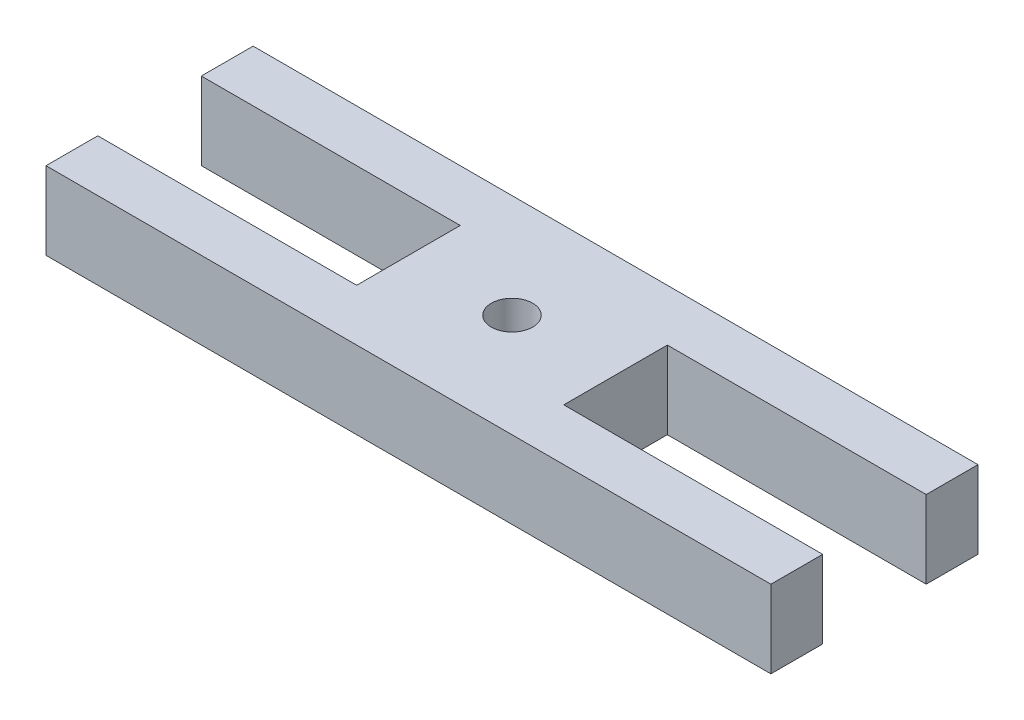
SolidWorks part; units mm, degrees
ref_plane "Front Plane" through (0, 0, 0) normal (0, 0, 1) x (1, 0, 0)
ref_plane "Top Plane" through (0, 0, 0) normal (0, 1, 0) x (1, 0, 0)
ref_plane "Right Plane" through (0, 0, 0) normal (1, 0, 0) x (0, 0, -1)
sketch "Sketch1" plane through (0, 0, 0) normal (0, 1, 0) x (1, 0, 0)
  line L12 (-27.5831, 22.4062) -> (-27.5831, 24.4062)
  line L25 (-20.5831, 25.4062) -> (-20.5831, 26.4062)
  line L26 (-20.5831, 25.4062) -> (-25.5831, 25.4062)
  line L27 (-25.5831, 25.4062) -> (-25.5831, 23.4062)
  line L28 (-25.5831, 23.4062) -> (-20.5831, 23.4062)
  line L29 (-20.5831, 23.4062) -> (-20.5831, 22.4062)
  line L30 (-20.5831, 22.4062) -> (-25.5831, 22.4062)
  line L31 (-20.5831, 26.4062) -> (-29.5308, 26.4062)
  line L32 (-25.5831, 22.4062) -> (-29.5831, 22.4062)
  line L33 (-20.5831, 26.4062) -> (-34.5831, 26.4062)
  line L34 (-20.5831, 22.4062) -> (-34.5831, 22.4062)
  line L35 (-34.5831, 22.4062) -> (-34.5831, 23.4062)
  line L36 (-34.5831, 23.4062) -> (-29.5831, 23.4062)
  line L37 (-29.5831, 23.4062) -> (-29.5831, 25.4062)
  line L38 (-29.5831, 25.4062) -> (-34.5831, 25.4062)
  line L39 (-34.5831, 25.4062) -> (-34.5831, 26.4062)
  circle A1 centre (-27.5831, 24.4062) radius 0.4
extrude "Boss-Extrude3" add sketch "Sketch1" along normal blind 1.5
